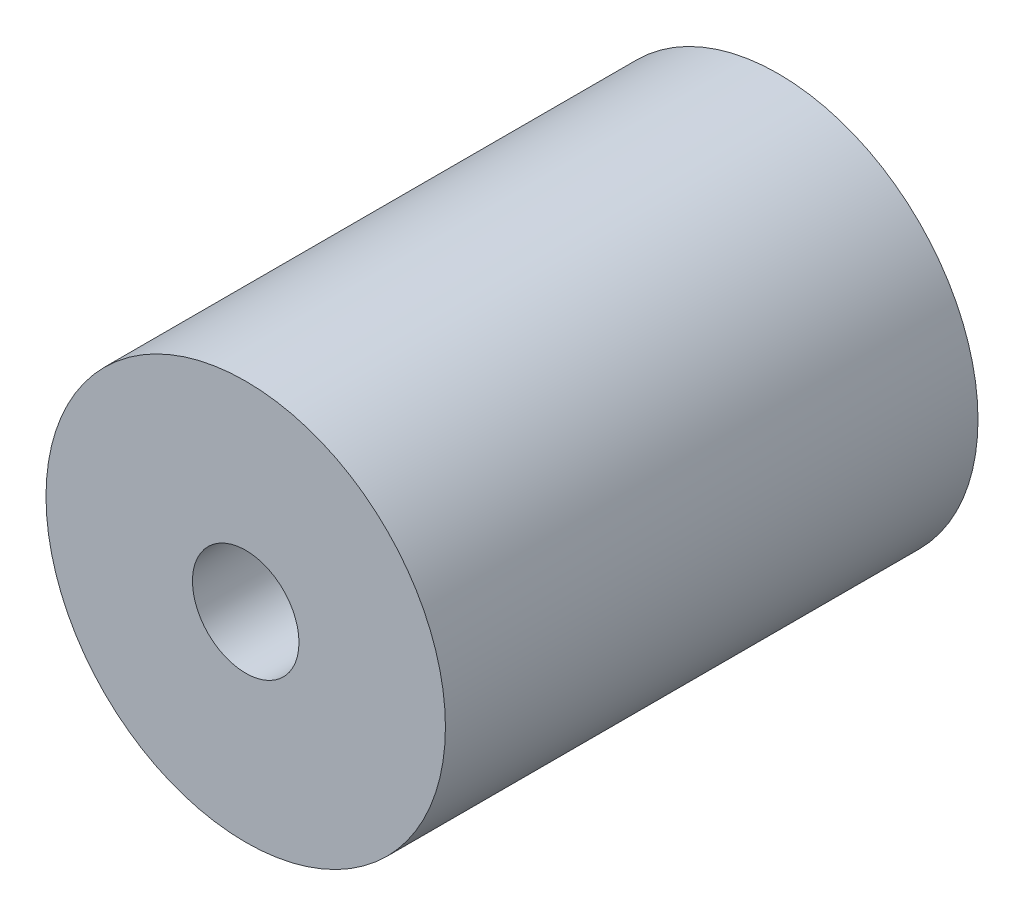
SolidWorks part; units mm, degrees
ref_plane "Front Plane" through (0, 0, 0) normal (0, 0, 1) x (1, 0, 0)
ref_plane "Top Plane" through (0, 0, 0) normal (0, 1, 0) x (1, 0, 0)
ref_plane "Right Plane" through (0, 0, 0) normal (1, 0, 0) x (0, 0, -1)
sketch "Esquisse1" plane through (0, 0, 0) normal (0, 0, 1) x (1, 0, 0)
  circle A0 centre (0, 0) radius 15
  dimension "D1" = 30
extrude "Boss.-Extru.1" add sketch "Esquisse1" along normal blind 40
sketch "Esquisse2" plane through (0, 0, 40) normal (0, 0, 1) x (1, 0, 0)
  circle A0 centre (0, 0) radius 4
  dimension "D1" = 8
extrude "Enlèv. mat.-Extru.1" cut sketch "Esquisse2" against normal blind 15
sketch "Esquisse3" plane through (0, 0, 0) normal (0, 0, -1) x (-1, 0, 0)
  circle A0 centre (0, 0) radius 6.35
  dimension "D1" = 12.7
extrude "Enlèv. mat.-Extru.2" cut sketch "Esquisse3" against normal blind 15
